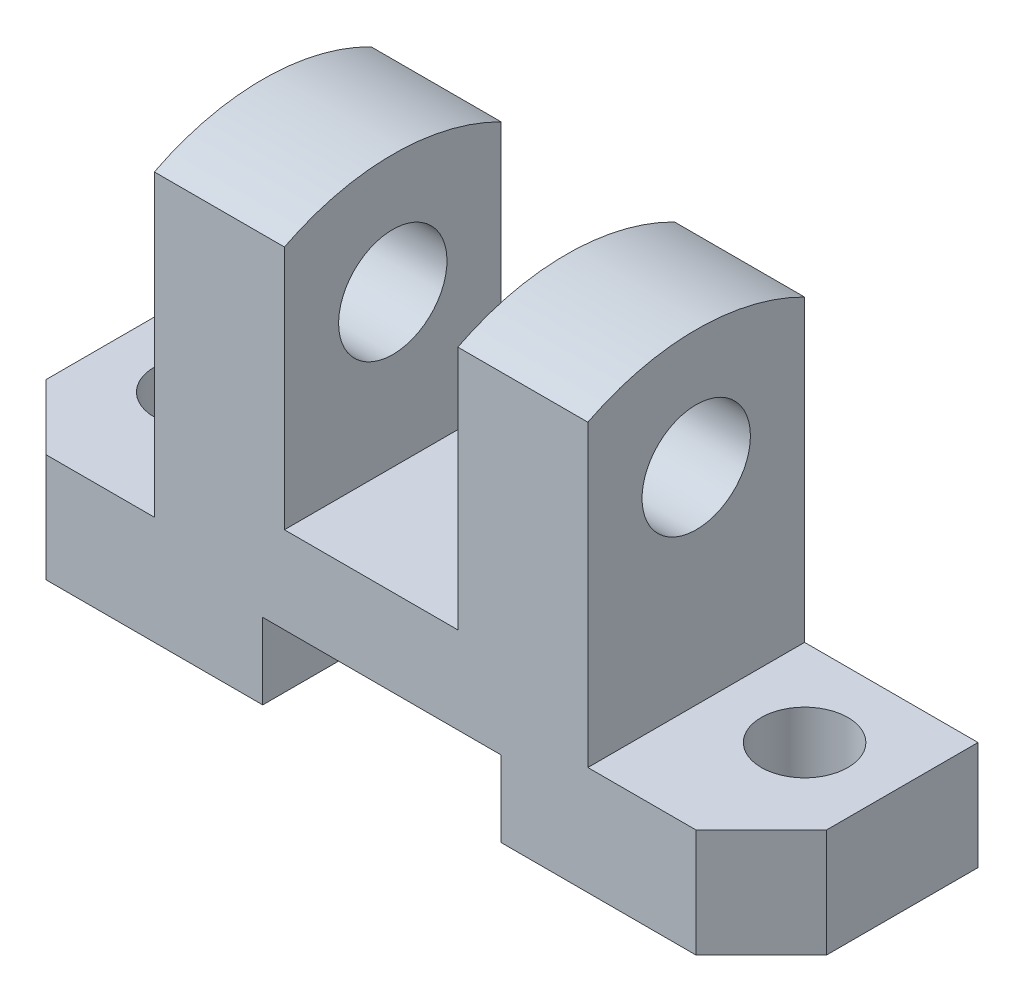
SolidWorks part; units mm, degrees
material "6063-T6"
ref_plane "Plan de face" through (0, 0, 0) normal (0, 0, 1) x (1, 0, 0)
ref_plane "Plan de dessus" through (0, 0, 0) normal (0, 1, 0) x (1, 0, 0)
ref_plane "Plan de droite" through (0, 0, 0) normal (1, 0, 0) x (0, 0, -1)
sketch "Esquisse1" plane through (0, 0, 0) normal (1, 0, 0) x (0, 0, -1)
  line L0 (-15.875, 59.6835) -> (-15.875, 0)
  line L1 (-15.875, 0) -> (15.875, 0)
  line L2 (15.875, 0) -> (15.875, 59.6835)
  arc A0 (-15.875, 59.6835) -> (15.875, 59.6835) centre (0, 28.575) cw
  point P6 (0, 0)
  point P7 (30.6966, 43.6573)
  point P8 (0, 0)
  point P9 (26.1004, 44.4593)
  point P10 (0, 0)
  dimension "D1" = 34.925
  dimension "D2" = 31.75
  dimension "D3" = 28.575
extrude "Boss.-Extru.1" add sketch "Esquisse1" along normal mid plane 114.3
sketch "Esquisse2" plane through (0, 0, 15.875) normal (0, 0, 1) x (1, 0, 0)
  line L0 (57.15, 63.5) -> (-57.15, 63.5) construction
  line L1 (57.15, 63.5) -> (31.75, 63.5)
  line L2 (57.15, 63.5) -> (57.15, 15.875)
  line L3 (57.15, 15.875) -> (31.75, 15.875)
  line L4 (31.75, 63.5) -> (31.75, 15.875)
  line L5 (-57.15, 63.5) -> (-31.75, 63.5)
  line L6 (-57.15, 63.5) -> (-57.15, 15.875)
  line L7 (-57.15, 15.875) -> (-31.75, 15.875)
  line L8 (-31.75, 63.5) -> (-31.75, 15.875)
  line L9 (-12.7, 63.5) -> (12.7, 63.5)
  line L10 (-12.7, 63.5) -> (-12.7, 23.8125)
  line L11 (-12.7, 23.8125) -> (12.7, 23.8125)
  line L12 (12.7, 63.5) -> (12.7, 23.8125)
  line L13 (57.15, 0) -> (-57.15, 0) construction
  line L14 (-15.875, 0) -> (19.05, 0)
  line L15 (-15.875, 0) -> (-15.875, 11.1125)
  line L16 (-15.875, 11.1125) -> (19.05, 11.1125)
  line L17 (19.05, 0) -> (19.05, 11.1125)
  point P24 (5.5973, 63.5)
  dimension "D1" = 25.4
  dimension "D2" = 19.05
  dimension "D3" = 25.4
  dimension "D4" = 38.1
  dimension "D5" = 34.925
  dimension "D6" = 11.1125
  dimension "D7" = 15.875
  dimension "D8" = 12.7
extrude "Enlèv. mat.-Extru.1" cut sketch "Esquisse2" against normal through all
chamfer "Chanfrein1" distance 9.525 angle 45 2 edges at (-57.15, 7.9375, 15.875) (57.15, 7.9375, 15.875)
hole_wizard "Diamètre du perçage 5/8 (0.625)2" positions "Esquisse5" profile "Esquisse6" hole size "5/8" standard "Ansi Inch" end condition through all
sketch "Esquisse5" plane through (31.75, 0, 0) normal (1, 0, 0) x (0, 0, -1)
  line L0 (-6.35, 0) -> (15.875, 0) construction
  point P0 (0, 46.0375)
  point P5 (0, 0)
  dimension "D1" = 46.0375
sketch "Esquisse6" plane through (31.75, 46.0375, 0) normal (0, 1, 0) x (0, 0, -1)
  line L0 (0, 0) -> (0, 88.9)
  line L1 (0, 88.9) -> (7.9375, 88.9)
  line L2 (7.9375, 88.9) -> (7.9375, 0)
  line L5 (7.9375, 0) -> (0, 0)
  line L11 (0, -6.35) -> (0, 107.95) construction
  dimension "Diamètre du perçage jusqu'au prochain" = 15.875
  dimension "Profondeur du perçage jusqu'au prochain" = 88.9
hole_wizard "Diamètre du perçage 1/2 (0.5)1" positions "Esquisse7" profile "Esquisse8" hole size "1/2" standard "Ansi Inch" end condition through all
sketch "Esquisse7" plane through (0, 15.875, 0) normal (0, 1, 0) x (1, 0, 0)
  line L0 (31.75, 15.875) -> (57.15, 15.875) construction
  line L1 (57.15, 15.875) -> (57.15, -6.35) construction
  point P0 (44.45, 3.175)
  dimension "D1" = 12.7
  dimension "D2" = 12.7
sketch "Esquisse8" plane through (44.45, 15.875, -3.175) normal (1, 0, 0) x (0, 0, 1)
  line L0 (0, 0) -> (0, 15.875)
  line L1 (0, 15.875) -> (6.35, 15.875)
  line L2 (6.35, 15.875) -> (6.35, 0)
  line L5 (6.35, 0) -> (0, 0)
  line L11 (0, -6.35) -> (0, 107.95) construction
  dimension "Diamètre du perçage jusqu'au prochain" = 12.7
  dimension "Profondeur du perçage jusqu'au prochain" = 15.875
mirror "Symétrie1" about plane through (0, 0, 0) normal (1, 0, 0) of "Diamètre du perçage 1/2 (0.5)1"
